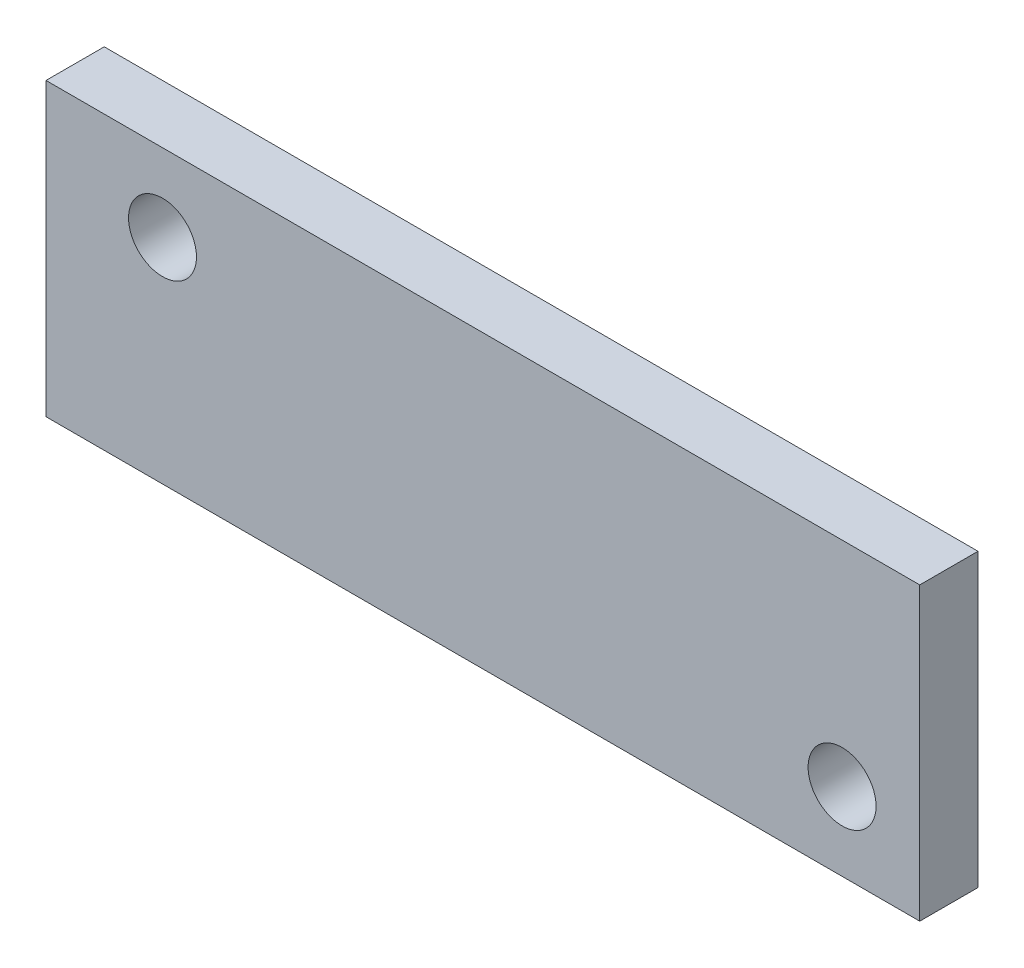
SolidWorks part; units mm, degrees
ref_plane "Front Plane" through (0, 0, 0) normal (0, 0, 1) x (1, 0, 0)
ref_plane "Top Plane" through (0, 0, 0) normal (0, 1, 0) x (1, 0, 0)
ref_plane "Right Plane" through (0, 0, 0) normal (1, 0, 0) x (0, 0, -1)
sketch "Sketch1" plane through (0, 0, 0) normal (0, 0, 1) x (1, 0, 0)
  line L1 (22.5, 7.5) -> (-22.5, 7.5)
  line L2 (22.5, 7.5) -> (22.5, -7.5)
  line L3 (22.5, -7.5) -> (-22.5, -7.5)
  line L4 (-22.5, 7.5) -> (-22.5, -7.5)
  line L5 (22.5, 7.5) -> (-22.5, -7.5) construction
  line L6 (22.5, -7.5) -> (-22.5, 7.5) construction
  point P0 (0, 0)
  dimension "D1" = 45
  dimension "D2" = 15
extrude "Boss-Extrude1" add sketch "Sketch1" along normal blind 3
sketch "Sketch3" plane through (0, 0, 3) normal (0, 0, 1) x (1, 0, 0)
  line L0 (22.5, -7.5) -> (22.5, 7.5) construction
  line L1 (-22.5, -7.5) -> (22.5, -7.5) construction
  circle A0 centre (18.5, -3.5) radius 1.75
  circle A1 centre (-16.5, 3.5) radius 1.75
  dimension "D1" = 3.5
  dimension "D2" = 3.5
  dimension "D3" = 4
  dimension "D4" = 4
  dimension "D5" = 35
  dimension "D6" = 7
extrude "Cut-Extrude1" cut sketch "Sketch3" against normal blind 3
